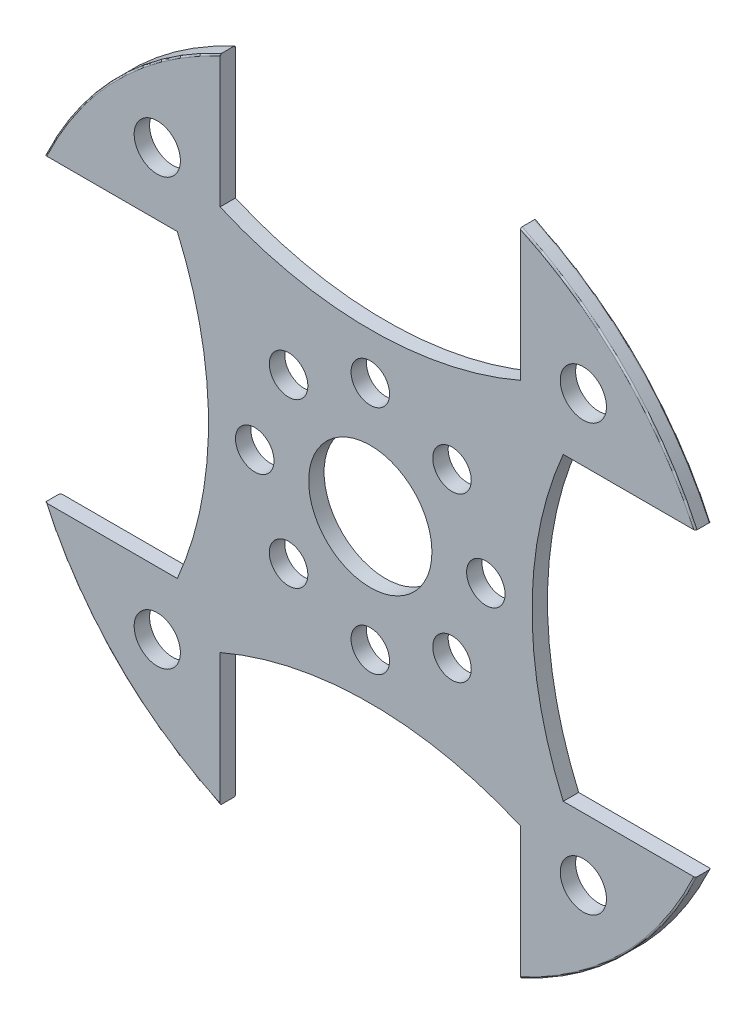
SolidWorks part; units mm, degrees
material "3.3549 (EN-AW 5182)"
ref_plane "Спереди" through (0, 0, 0) normal (0, 0, 1) x (1, 0, 0)
ref_plane "Сверху" through (0, 0, 0) normal (0, 1, 0) x (1, 0, 0)
ref_plane "Справа" through (0, 0, 0) normal (1, 0, 0) x (0, 0, -1)
sketch "Эскиз1" plane through (0, 0, 0) normal (0, 0, 1) x (1, 0, 0)
  line L0 (16.4402, 16.4402) -> (13.8257, 13.8257) construction
  line L1 (21.1069, 9.75) -> (12.5236, 9.75)
  line L2 (12.5236, -9.75) -> (21.1069, -9.75)
  line L3 (9.75, -21.1069) -> (9.75, -12.5236)
  line L4 (-9.75, -12.5236) -> (-9.75, -21.1069)
  line L5 (-21.1069, -9.75) -> (-12.5236, -9.75)
  line L6 (-12.5236, 9.75) -> (-21.1069, 9.75)
  line L7 (-9.75, 21.1069) -> (-9.75, 12.5236)
  line L8 (9.75, 12.5236) -> (9.75, 21.1069)
  arc A0 (21.1069, 9.75) -> (9.75, 21.1069) centre (0, 0) ccw
  circle A1 centre (0, 0) radius 4
  circle A2 centre (0, 0) radius 7.5 construction
  circle A3 centre (0, 7.5) radius 1.25
  circle A4 centre (5.3033, 5.3033) radius 1.25
  circle A5 centre (7.5, 0) radius 1.25
  circle A6 centre (5.3033, -5.3033) radius 1.25
  circle A7 centre (0, -7.5) radius 1.25
  circle A8 centre (-5.3033, -5.3033) radius 1.25
  circle A9 centre (-7.5, 0) radius 1.25
  circle A10 centre (-5.3033, 5.3033) radius 1.25
  arc A11 (12.8542, 9.25) -> (12.8542, -9.25) centre (35, 0) ccw construction
  arc A12 (12.5236, 9.75) -> (12.5236, -9.75) centre (35, 0) ccw
  arc A13 (9.75, -12.5236) -> (-9.75, -12.5236) centre (0, -35) ccw
  arc A14 (-12.5236, -9.75) -> (-12.5236, 9.75) centre (-35, 0) ccw
  arc A15 (-9.75, 12.5236) -> (9.75, 12.5236) centre (0, 35) ccw
  arc A16 (-9.75, 21.1069) -> (-21.1069, 9.75) centre (0, 0) ccw
  arc A17 (-21.1069, -9.75) -> (-9.75, -21.1069) centre (0, 0) ccw
  arc A18 (9.75, -21.1069) -> (21.1069, -9.75) centre (0, 0) ccw
  circle A19 centre (13.8257, 13.8257) radius 1.5
  circle A20 centre (13.8257, -13.8257) radius 1.5
  circle A21 centre (-13.8257, -13.8257) radius 1.5
  circle A22 centre (-13.8257, 13.8257) radius 1.5
  point P22 (0, 0)
  point P46 (0, 0)
  point P53 (0, 0)
  dimension "D1" = 46.5
  dimension "D2" = 8
  dimension "D3" = 15
  dimension "D4" = 2.5
  dimension "D5" = 3
extrude "Бобышка-Вытянуть1" add sketch "Эскиз1" along normal blind 1
fillet "Скругление1" radius 0.1 8 edges at (16.4402, -16.4402, 1) (16.4402, -16.4402, 0) (-16.4402, -16.4402, 1) (-16.4402, -16.4402, 0) (-16.4402, 16.4402, 0) (-16.4402, 16.4402, 1) (16.4402, 16.4402, 0) (16.4402, 16.4402, 1)
